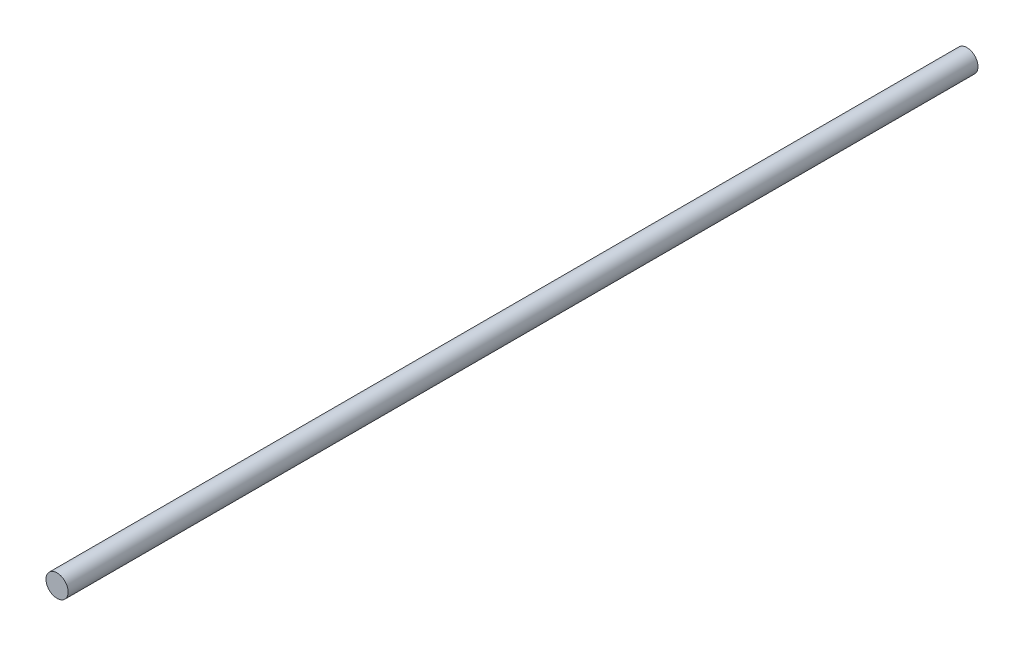
SolidWorks part; units mm, degrees
ref_plane "Front Plane" through (0, 0, 0) normal (0, 0, 1) x (1, 0, 0)
ref_plane "Top Plane" through (0, 0, 0) normal (0, 1, 0) x (1, 0, 0)
ref_plane "Right Plane" through (0, 0, 0) normal (1, 0, 0) x (0, 0, -1)
sketch "Sketch2" plane through (0, 0, 0) normal (0, 0, 1) x (1, 0, 0)
  circle A0 centre (0, 0) radius 6.45
  dimension "D1" = 12.9
extrude "Boss-Extrude1" add sketch "Sketch2" along normal blind 530
